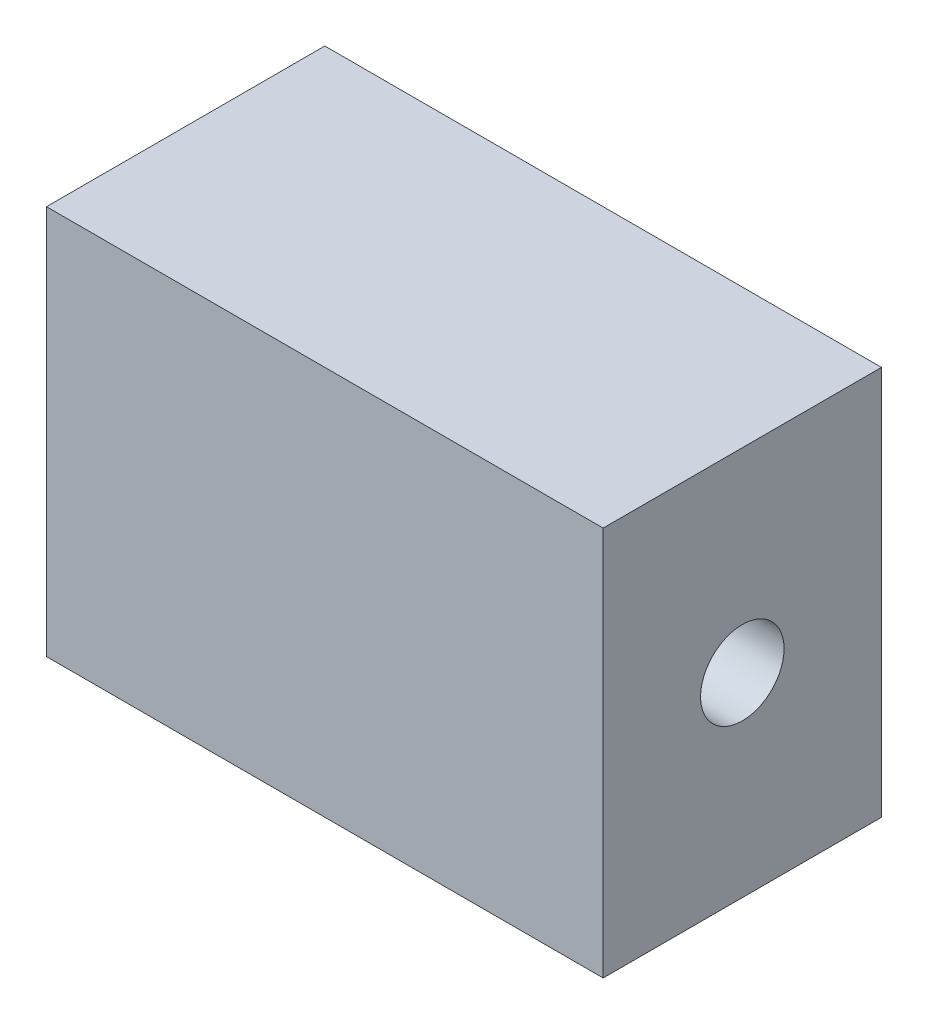
SolidWorks part; units mm, degrees
ref_plane "Front Plane" through (0, 0, 0) normal (0, 0, 1) x (1, 0, 0)
ref_plane "Top Plane" through (0, 0, 0) normal (0, 1, 0) x (1, 0, 0)
ref_plane "Right Plane" through (0, 0, 0) normal (1, 0, 0) x (0, 0, -1)
sketch "Sketch1" plane through (0, 0, 0) normal (0, 0, 1) x (1, 0, 0)
  line L0 (0, 0) -> (0, 70)
  line L1 (0, 70) -> (100, 70)
  line L2 (100, 70) -> (100, 0)
  line L3 (100, 0) -> (0, 0)
  dimension "D1" = 100
  dimension "D2" = 70
extrude "Boss-Extrude1" add sketch "Sketch1" along normal blind 50
sketch "Sketch2" plane through (100, 0, 0) normal (1, 0, 0) x (0, 0, -1)
  line L0 (-50, 70) -> (0, 70) construction
  line L1 (-50, 0) -> (-50, 70) construction
  circle A0 centre (-25, 35) radius 7.5
  dimension "D1" = 35
  dimension "D3" = 15
  dimension "D2" = 25
extrude "Cut-Extrude1" cut sketch "Sketch2" against normal blind 100 contours A0
sketch "Sketch3" plane through (0, 0, 0) normal (0, 0, -1) x (-1, 0, 0)
  line L0 (-90, 60) -> (-90, 10)
  line L3 (-90, 10) -> (-10, 10)
  line L4 (-10, 10) -> (-10, 60)
  line L5 (-10, 60) -> (-90, 60)
  line L6 (0, 70) -> (0, 0) construction
  line L7 (0, 0) -> (-100, 0) construction
  dimension "D1" = 80
  dimension "D2" = 50
  dimension "D3" = 10
  dimension "D4" = 10
extrude "Cut-Extrude2" cut sketch "Sketch3" against normal blind 10
